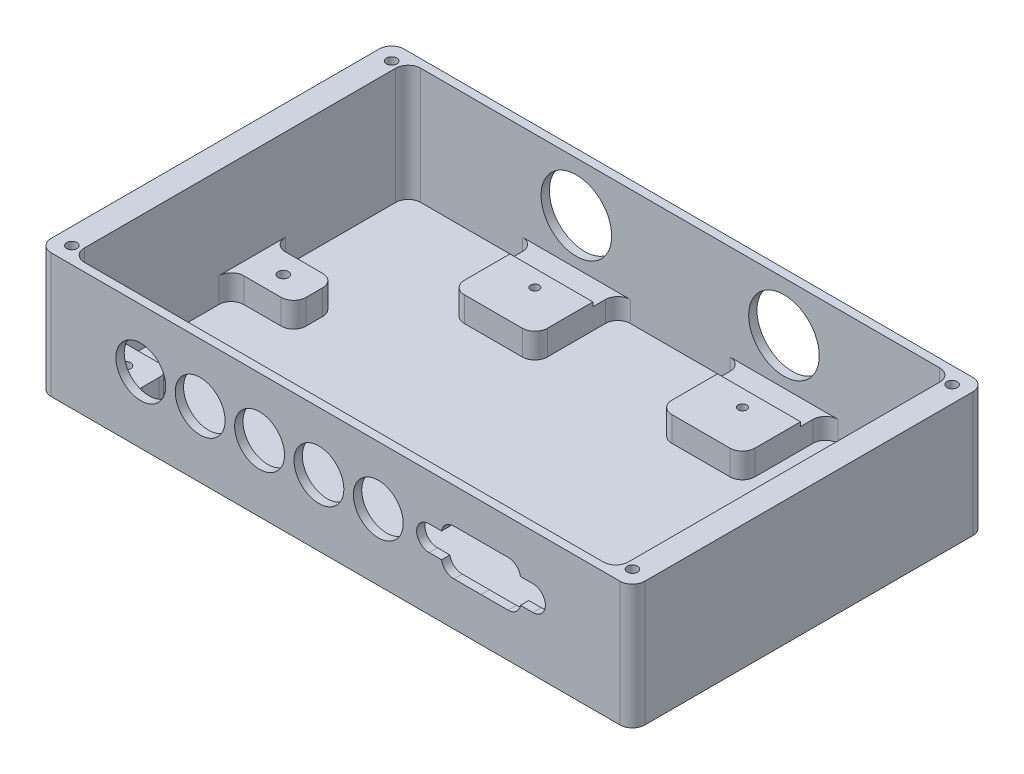
SolidWorks part; units mm, degrees
ref_plane "Ebene vorne" through (0, 0, 0) normal (0, 0, 1) x (1, 0, 0)
ref_plane "Ebene oben" through (0, 0, 0) normal (0, 1, 0) x (1, 0, 0)
ref_plane "Ebene rechts" through (0, 0, 0) normal (1, 0, 0) x (0, 0, -1)
sketch "Skizze1" plane through (0, 0, 0) normal (0, 1, 0) x (1, 0, 0)
  line L1 (0, 0) -> (135, 0)
  line L2 (0, 0) -> (0, 85)
  line L3 (0, 85) -> (135, 85)
  line L4 (135, 0) -> (135, 85)
  dimension "D1" = 85
  dimension "D2" = 135
extrude "Aufsatz-Linear austragen1" add sketch "Skizze1" along normal blind 30
shell "Schale1" thickness 2
sketch "Skizze2" plane through (0, 0, 0) normal (0, 0, 1) x (1, 0, 0)
  line L0 (4.8493, 15.94) -> (121.4088, 15.94) construction
  line L1 (0, 0) -> (135, 0) construction
  line L2 (0, 30) -> (0, 0) construction
  circle A0 centre (20.6, 15.94) radius 6
  circle A1 centre (34.9, 15.94) radius 6
  circle A2 centre (49.2, 15.94) radius 6
  circle A3 centre (63.5, 15.94) radius 6
  circle A4 centre (77.8, 15.94) radius 6
  dimension "D2" = 12
  dimension "D3" = 20.6
  dimension "D4" = 34.9
  dimension "D5" = 49.2
  dimension "D6" = 63.5
  dimension "D7" = 77.8
  dimension "D8" = 12
  dimension "D9" = 12
  dimension "D10" = 12
  dimension "D11" = 12
  dimension "D1" = 15.94
extrude "Schnitt-Linear austragen1" cut sketch "Skizze2" against normal blind 30
sketch "Skizze3" plane through (0, 0, 0) normal (0, 0, 1) x (1, 0, 0)
  line L0 (102.5402, 21.49) -> (95.9981, 21.49)
  line L1 (93.0401, 18.99) -> (90.04, 18.99)
  line L2 (0, 30) -> (0, 0) construction
  line L3 (87.04, 15.99) -> (134.747, 15.99) construction
  line L5 (102.5399, 11.9127) -> (102.5402, 21.49) construction
  line L7 (102.5402, 10.49) -> (95.9981, 10.49)
  line L8 (93.0401, 12.99) -> (90.04, 12.99)
  line L9 (102.5395, 10.49) -> (109.0816, 10.4896)
  line L10 (102.5402, 21.49) -> (109.0822, 21.4896)
  line L11 (112.0398, 12.9895) -> (115.0398, 12.9893)
  line L12 (112.0401, 18.9895) -> (115.0402, 18.9893)
  arc A0 (95.9981, 21.49) -> (93.0401, 18.99) centre (95.9981, 18.49) ccw
  arc A1 (90.04, 18.99) -> (90.04, 12.99) centre (90.04, 15.99) ccw
  arc A2 (95.9981, 10.49) -> (93.0401, 12.99) centre (95.9981, 13.49) cw
  arc A3 (109.0816, 10.4896) -> (112.0398, 12.9895) centre (109.0817, 13.4896) ccw
  arc A4 (115.0402, 18.9893) -> (115.0398, 12.9893) centre (115.04, 15.9893) cw
  arc A5 (109.0822, 21.4896) -> (112.0401, 18.9895) centre (109.082, 18.4896) cw
  point P12 (87.04, 15.99)
  dimension "D7" = 3
  dimension "D1" = 5.5
  dimension "D2" = 9.5
  dimension "D3" = 3
  dimension "D4" = 15.99
  dimension "D5" = 87.04
  dimension "D6" = 15.5
extrude "Schnitt-Linear austragen2" cut sketch "Skizze3" against normal blind 10 contours A5 L10 L0 A0 L1 A1 L8 A2 L7 L9 A3 L11 A4 L12
fillet "Verrundung1" radius 3 8 edges at (0, 15, -85) (135, 15, -85) (135, 15, 0) (0, 15, 0) (133, 16, -2) (133, 16, -83) (2, 16, -83) (2, 16, -2)
sketch "Skizze4" plane through (0, 2, 0) normal (0, 1, 0) x (1, 0, 0)
  line L0 (2, 12) -> (13, 12)
  line L1 (2, 80) -> (2, 5) construction
  line L2 (16, 9) -> (16, 2)
  line L3 (5, 2) -> (130, 2) construction
  line L5 (5, 2) -> (16, 2)
  line L6 (2, 12) -> (2, 5)
  line L7 (67.5, 0) -> (67.5, 20.7722) construction
  line L8 (3, 0) -> (132, 0) construction
  line L9 (133, 12) -> (133, 5)
  line L10 (130, 2) -> (119, 2)
  line L11 (119, 9) -> (119, 2)
  line L12 (133, 12) -> (122, 12)
  arc A1 (13, 12) -> (16, 9) centre (13, 9) cw
  arc A2 (2, 5) -> (5, 2) centre (5, 5) ccw construction
  arc A3 (2, 5) -> (5, 2) centre (5, 5) ccw
  arc A4 (133, 5) -> (130, 2) centre (130, 5) cw
  arc A5 (122, 12) -> (119, 9) centre (122, 9) ccw
  point P13 (16, 12)
  line M4 (5, 2) -> (130, 2)
  arc M5 (130, 2) -> (133, 5) centre (130, 5) ccw
  line M6 (133, 5) -> (133, 80)
  line M10 (2, 80) -> (2, 5)
  arc M11 (2, 5) -> (5, 2) centre (5, 5) ccw
  dimension "D5" = 3
  dimension "D3" = 14
  dimension "D4" = 10
extrude "Aufsatz-Linear austragen2" add sketch "Skizze4" along normal blind 6 contours A1 L0 L2 M10 M11 M4 | L12 A5 L11 M4 M5 M6
fillet "Verrundung2" radius 3 4 edges at (133, 5, -12) (119, 5, -2) (16, 5, -2) (2, 5, -12)
sketch "Skizze5" plane through (0, 2, 0) normal (0, 1, 0) x (1, 0, 0)
  line L0 (2, 80) -> (2, 5) construction
  line L1 (2, 50.4) -> (17, 50.4)
  line L2 (2, 50.4) -> (2, 40.4)
  line L3 (2, 40.4) -> (17, 40.4)
  line L4 (17, 50.4) -> (17, 40.4)
  line L5 (16, 7) -> (7.9271, 7) construction
  line L6 (16, 9) -> (16, 5) construction
  line L7 (17, 45.4) -> (7.9271, 45.4) construction
  line L8 (67.5, 0) -> (67.5, 60.7015) construction
  line L9 (3, 0) -> (132, 0) construction
  line L10 (118, 50.4) -> (118, 40.4)
  line L11 (133, 40.4) -> (118, 40.4)
  line L12 (133, 50.4) -> (133, 40.4)
  line L13 (133, 50.4) -> (118, 50.4)
  dimension "D1" = 38.4
  dimension "D2" = 10
  dimension "D3" = 15
extrude "Aufsatz-Linear austragen3" add sketch "Skizze5" along normal blind 6
fillet "Verrundung3" radius 3 8 edges at (133, 5, -40.4) (133, 5, -50.4) (118, 5, -40.4) (118, 5, -50.4) (2, 5, -50.4) (17, 5, -50.4) (17, 5, -40.4) (2, 5, -40.4)
sketch "Skizze6" plane through (0, 0, -85) normal (0, 0, -1) x (-1, 0, 0)
  line L0 (-128.5127, 18) -> (-8.2871, 18) construction
  line L1 (-132, 0) -> (-3, 0) construction
  line L2 (-67.5, 0) -> (-67.5, 33.8667) construction
  circle A0 centre (-92.5, 18) radius 8.5
  circle A1 centre (-42.5, 18) radius 8.5
  dimension "D2" = 17
  dimension "D3" = 50
  dimension "D1" = 18
extrude "Schnitt-Linear austragen3" cut sketch "Skizze6" against normal blind 5
sketch "Skizze7" plane through (0, 2, 0) normal (0, 1, 0) x (1, 0, 0)
  line L0 (67.5, 85) -> (67.5, 35.1088) construction
  line L1 (132, 85) -> (3, 85) construction
  line L2 (130, 83) -> (5, 83) construction
  line L3 (32.5, 63) -> (52.5, 63)
  line L4 (32.5, 63) -> (32.5, 83)
  line L5 (32.5, 83) -> (52.5, 83)
  line L6 (52.5, 63) -> (52.5, 83)
  line L7 (42.5, 63) -> (42.5, 71.5986) construction
  line L8 (0, 82) -> (0, 3) construction
  line L9 (32.5, 63) -> (32.5, 83)
  line L10 (52.5, 63) -> (52.5, 83)
  line L11 (102.5, 83) -> (82.5, 83)
  line L12 (82.5, 63) -> (82.5, 83)
  line L13 (102.5, 63) -> (82.5, 63)
  line L14 (102.5, 63) -> (102.5, 83)
  line M17 (130, 83) -> (5, 83)
  dimension "D1" = 42.5
  dimension "D2" = 20
  dimension "D3" = 20
extrude "Aufsatz-Linear austragen4" add sketch "Skizze7" along normal blind 6 contours L3 L6 L4 M17 | L13 L14 L12 M17
fillet "Verrundung4" radius 3 8 edges at (102.5, 5, -83) (102.5, 5, -63) (82.5, 5, -63) (82.5, 5, -83) (32.5, 5, -83) (32.5, 5, -63) (52.5, 5, -83) (52.5, 5, -63)
hole_wizard "M3 Gewindebohrung1" positions "Skizze8" profile "Skizze9" tap size "M3" standard "DIN"
sketch "Skizze8" plane through (0, 8, 0) normal (0, 1, 0) x (1, 0, 0)
  line L1 (125.5, 7.4) -> (9.5, 7.4) construction
  line L2 (125.5, 7.4) -> (125.5, 45.4) construction
  line L3 (125.5, 45.4) -> (9.5, 45.4) construction
  line L4 (9.5, 7.4) -> (9.5, 45.4) construction
  line L5 (19, 2) -> (116, 2) construction
  line L6 (133, 15) -> (133, 37.4) construction
  line L7 (67.5, 0) -> (67.5, 59.3993) construction
  line L8 (3, 0) -> (132, 0) construction
  point P1 (125.5, 7.4)
  point P2 (9.5, 45.4)
  point P117 (125.5, 45.4)
  point P118 (9.5, 7.4)
  dimension "D1" = 5.4
  dimension "D2" = 7.5
  dimension "D3" = 38
  dimension "D4" = 116
sketch "Skizze9" plane through (125.5, 8, -7.4) normal (1, 0, 0) x (0, 0, 1)
  line L0 (0, 0) -> (0, 9.2511)
  line L1 (0, 9.2511) -> (1.25, 8.5)
  line L2 (1.25, 8.5) -> (1.25, 0)
  line L5 (1.25, 0) -> (0, 0)
  line L10 (0, 9.2511) -> (-1.25, 8.5) construction
  line L11 (0, -6.35) -> (0, 107.95) construction
  dimension "Bohrerdurchmesser" = 2.5
  dimension "Bohrungstiefe" = 8.5
  dimension "Spitzenwinkel" = 118
cosmetic thread "Bohrungsgewinde1" parameters "D1"=6, "D2"=3
cosmetic thread "Bohrungsgewinde2" parameters "D1"=6, "D2"=3
cosmetic thread "Bohrungsgewinde3" parameters "D1"=6, "D2"=3
cosmetic thread "Bohrungsgewinde4" parameters "D1"=6, "D2"=3
hole_wizard "M2.5 Gewindebohrung1" positions "Skizze10" profile "Skizze11" tap size "M2.5" standard "DIN"
sketch "Skizze10" plane through (0, 8, 0) normal (0, 1, 0) x (1, 0, 0)
  line L0 (92.5, 63) -> (92.5, 83) construction
  line L1 (99.5, 63) -> (85.5, 63) construction
  line L2 (42.5, 63) -> (42.5, 83) construction
  line L3 (35.5, 63) -> (49.5, 63) construction
  line L4 (105.5, 83) -> (79.5, 83) construction
  point P10 (92.5, 73)
  point P12 (42.5, 73)
  dimension "D1" = 10
sketch "Skizze11" plane through (42.5, 8, -73) normal (1, 0, 0) x (0, 0, 1)
  line L0 (0, 0) -> (0, 7.8659)
  line L1 (0, 7.8659) -> (1.025, 7.25)
  line L2 (1.025, 7.25) -> (1.025, 0)
  line L5 (1.025, 0) -> (0, 0)
  line L10 (0, 7.8659) -> (-1.025, 7.25) construction
  line L11 (0, -6.35) -> (0, 107.95) construction
  dimension "Bohrerdurchmesser" = 2.05
  dimension "Bohrungstiefe" = 7.25
  dimension "Spitzenwinkel" = 118
cosmetic thread "Bohrungsgewinde5" parameters "D1"=5, "D2"=2.5
cosmetic thread "Bohrungsgewinde6" parameters "D1"=5, "D2"=2.5
sketch "Skizze12" plane through (0, 8, 0) normal (0, 1, 0) x (1, 0, 0)
  line L0 (130, 83) -> (105.5, 83) construction
  line L1 (108.8489, 83) -> (23.8489, 83)
  line L2 (108.8489, 83) -> (108.8489, 77)
  line L3 (108.8489, 77) -> (23.8489, 77)
  line L4 (23.8489, 83) -> (23.8489, 77)
  dimension "D1" = 6
  dimension "D2" = 85
extrude "Schnitt-Linear austragen4" cut sketch "Skizze12" against normal blind 1
sketch "Skizze13" plane through (0, 2, 0) normal (0, 1, 0) x (1, 0, 0)
  line L0 (135.5425, 25) -> (-12.435, 25) construction
  line L1 (67.5, 0) -> (67.5, 38.2299) construction
  line L2 (3, 0) -> (132, 0) construction
  circle A0 centre (97.5, 25) radius 3.2
  circle A1 centre (37.5, 25) radius 3.2
  dimension "D1" = 6.4
  dimension "D2" = 30
  dimension "D3" = 25
extrude "Schnitt-Linear austragen5" cut sketch "Skizze13" against normal blind 10
sketch "Skizze14" plane through (0, 0, 0) normal (0, -1, 0) x (1, 0, 0)
  line L1 (0, -85) -> (-4, -85)
  line L2 (0, -82) -> (0, -3)
  line L3 (0, 0) -> (-4, 0)
  line L4 (-4, -85) -> (-4, 0)
  line L5 (135, 0) -> (139, 0)
  line L6 (135, -3) -> (135, -82)
  line L7 (135, -85) -> (139, -85)
  line L8 (139, 0) -> (139, -85)
  line L10 (3, 0) -> (0, 0)
  line L11 (3, -85) -> (0, -85)
  line L13 (135, 0) -> (132, 0)
  line L14 (135, -85) -> (132, -85)
  arc A0 (3, 0) -> (0, -3) centre (3, -3) ccw
  arc A1 (0, -82) -> (3, -85) centre (3, -82) ccw
  arc A2 (132, -85) -> (135, -82) centre (132, -82) ccw
  arc A4 (132, 0) -> (135, -3) centre (132, -3) cw
extrude "Aufsatz-Linear austragen5" add sketch "Skizze14" against normal up to surface (30 mm away) up to face at (67.5, 30, -42.5)
hole_wizard "M3 Gewindebohrung2" positions "Skizze16" profile "Skizze18" tap size "M3" standard "DIN"
sketch "Skizze16" plane through (76.7448, 30, -27.1141) normal (0, 1, 0) x (1, 0, 0)
  line L1 (-76.7448, -23.1141) -> (58.2552, -23.1141) construction
  line L2 (-76.7448, -23.1141) -> (-76.7448, 53.8859) construction
  line L3 (-76.7448, 53.8859) -> (58.2552, 53.8859) construction
  line L4 (58.2552, -23.1141) -> (58.2552, 53.8859) construction
  line L9 (62.2552, -27.1141) -> (62.2552, 57.8859) construction
  line L10 (-80.7448, 57.8859) -> (-80.7448, -27.1141) construction
  line L11 (62.2552, 57.8859) -> (-80.7448, 57.8859) construction
  line L12 (-80.7448, -27.1141) -> (62.2552, -27.1141) construction
  point P0 (-76.7448, -23.1141)
  point P1 (58.2552, 53.8859)
  point P106 (-76.7448, 53.8859)
  point P107 (58.2552, -23.1141)
  point P120 (0, 0)
  dimension "D1" = 4
  dimension "D2" = 4
  dimension "D3" = 4
  dimension "D4" = 4
sketch "Skizze18" plane through (0, 30, -4) normal (1, 0, 0) x (0, 0, 1)
  line L0 (0, 0) -> (0, 9.2511)
  line L1 (0, 9.2511) -> (1.25, 8.5)
  line L2 (1.25, 8.5) -> (1.25, 0)
  line L5 (1.25, 0) -> (0, 0)
  line L10 (0, 9.2511) -> (-1.25, 8.5) construction
  line L11 (0, -6.35) -> (0, 107.95) construction
  dimension "Bohrerdurchmesser" = 2.5
  dimension "Bohrungstiefe" = 8.5
  dimension "Spitzenwinkel" = 118
cosmetic thread "Bohrungsgewinde7" parameters "D1"=6, "D2"=3
cosmetic thread "Bohrungsgewinde8" parameters "D1"=6, "D2"=3
cosmetic thread "Bohrungsgewinde9" parameters "D1"=6, "D2"=3
cosmetic thread "Bohrungsgewinde10" parameters "D1"=6, "D2"=3
fillet "Verrundung5" radius 3 4 edges at (139, 15, 0) (-4, 15, 0) (-4, 15, -85) (139, 15, -85)
